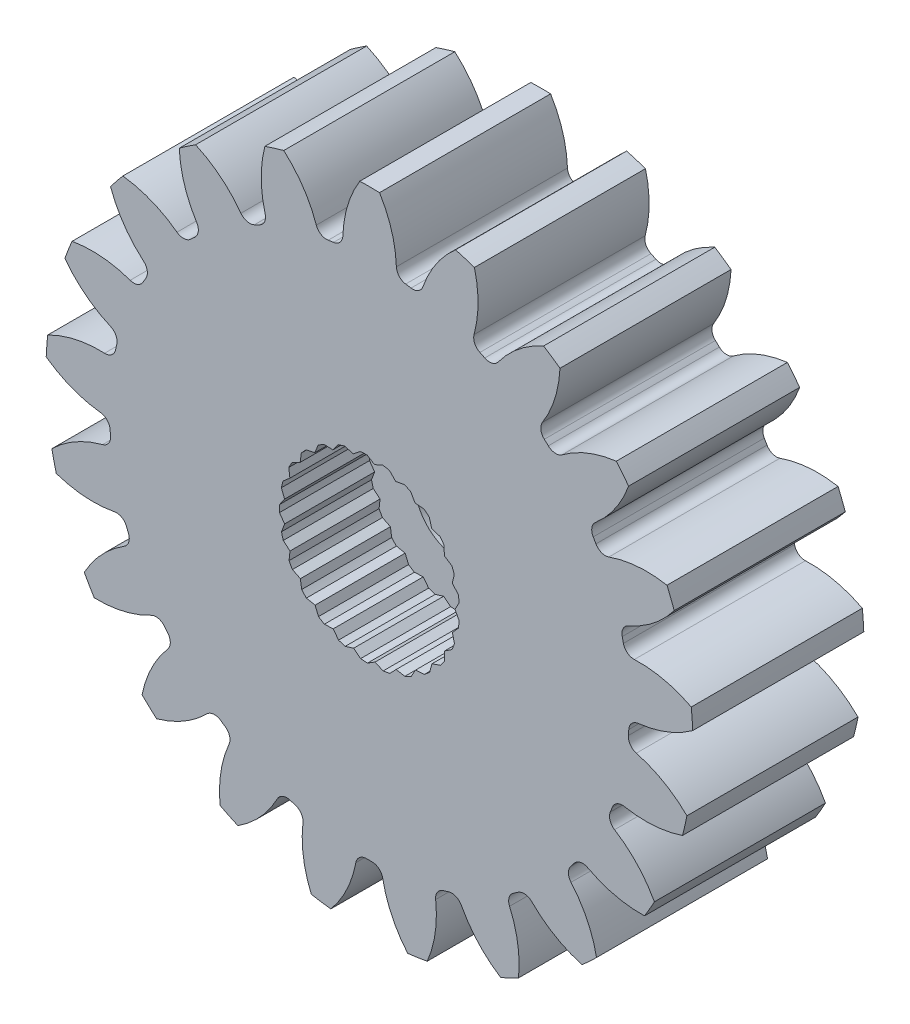
SolidWorks part; units mm, degrees
ref_plane "Front" through (0, 0, 0) normal (0, 0, 1) x (1, 0, 0)
ref_plane "Top" through (0, 0, 0) normal (0, 1, 0) x (1, 0, 0)
ref_plane "Right" through (0, 0, 0) normal (1, 0, 0) x (0, 0, -1)
sketch "Sketch3" plane through (0, 0, 0) normal (0, 0, 1) x (1, 0, 0)
  circle A0 centre (0, 0) radius 9.1281
  dimension "od" = 18.2562
extrude "gearBody" add sketch "Sketch3" along normal blind 4.826
sketch "Sketch2" plane through (0, 0, 0) normal (0, 0, 1) x (1, 0, 0)
  line L0 (0, 0) -> (7.2356, 2.9971) construction
  line L1 (9.5965, -2.6604) -> (0, 0) construction
  line L2 (0, 0) -> (36.3143, 0) construction
  line L3 (8.3344, -0.0188) -> (8.2426, -1.2336) construction
  line L5 (8.2885, -0.6262) -> (0, 0) construction
  line L7 (0, 0) -> (7.8318, 0) construction
  arc A0 (7.8302, -0.1572) -> (7.7649, -1.021) centre (0, 0) ccw construction
  arc A1 (9.1194, 0.3982) -> (8.9561, -1.7638) centre (0, 0) ccw construction
  arc A2 (8.3344, -0.0188) -> (8.2426, -1.2336) centre (0, 0) ccw construction
  arc A3 (7.3041, -0.6287) -> (7.3156, -0.4758) centre (0, 0) ccw
  arc A4 (9.5965, -2.6604) -> (7.5285, -0.9483) centre (6.7032, -4.0501) ccw
  arc A5 (9.5965, -2.6604) -> (9.8873, 1.1884) centre (0, 0) ccw
  arc A6 (9.8873, 1.1884) -> (7.5856, -0.1936) centre (7.2356, 2.9971) cw
  arc A7 (7.3156, -0.4758) -> (7.5856, -0.1936) centre (7.6187, -0.4955) cw
  arc A8 (7.5285, -0.9483) -> (7.3041, -0.6287) centre (7.6066, -0.6548) cw
  point P6 (9.8873, 1.1884)
  point P22 (9.5965, -2.6604)
  dimension "baseDia" = 15.6635
  dimension "od" = 18.2562
  dimension "pd" = 16.6687
  dimension "rd" = 14.6622
  dimension "rFillet" = 0.3037
  dimension "pointX" = 9.8873
  dimension "pointY" = 1.1884
  dimension "CTT" = 1.2148
  dimension "flankCenterAngle" = 22.5
extrude "toothCut" cut sketch "Sketch2" along normal through all
pattern_circular "CirPattern1" count 21 over 360 about axis through (0, 0, 0) along (0, 0, 1) of "toothCut"
sketch "hub1Dia" plane through (0, 0, 0) normal (0, 0, -1) x (-1, 0, 0)
  circle A0 centre (0, 0) radius 12.7
  dimension "hub1Dia" = 25.4
sketch "hub2Dia" plane through (0, 0, 4.826) normal (0, 0, 1) x (1, 0, 0)
  circle A0 centre (0, 0) radius 12.7
  dimension "hub2dia" = 25.4
sketch "boreDia" plane through (0, 0, 0) normal (0, 0, 1) x (1, 0, 0)
  circle A0 centre (0, 0) radius 3.175
  dimension "boreDia" = 6.35
extrude "bore" cut sketch "boreDia" against normal mid plane 25400
sketch "Sketch5" plane through (0, 0, 0) normal (0, 0, -1) x (-1, 0, 0)
  circle A0 centre (0, 0) radius 1.27
  circle A1 centre (0, 0) radius 3.175
  dimension "D1" = 2.54
extrude "Boss-Extrude2" add sketch "Sketch5" against normal up to surface (4.826 mm away) up to face at (3.175, 0, 4.826)
sketch "Sketch4" plane through (0, 0, 4.826) normal (0, 0, 1) x (1, 0, 0)
  line L100 (-2.484, 0.5306) -> (-2.3947, 0.2965)
  line L101 (-2.2457, 0.8827) -> (-2.4359, 0.7196)
  line L102 (-2.274, 1.1317) -> (-2.2457, 0.8827)
  line L103 (-1.9557, 1.4135) -> (-2.1804, 1.3028)
  line L104 (-1.9211, 1.6616) -> (-1.9557, 1.4135)
  line L105 (-1.5427, 1.8554) -> (-1.788, 1.8041)
  line L106 (-1.4475, 2.0872) -> (-1.5427, 1.8554)
  line L107 (-1.0328, 2.1808) -> (-1.2831, 2.1921)
  line L108 (-0.883, 2.3816) -> (-1.0328, 2.1808)
  line L109 (-0.458, 2.3691) -> (-0.6977, 2.4423)
  line L110 (-0.263, 2.5264) -> (-0.458, 2.3691)
  line L111 (0.1455, 2.4086) -> (-0.0684, 2.5391)
  line L112 (0.3736, 2.5124) -> (0.1455, 2.4086)
  line L113 (0.74, 2.2967) -> (0.5652, 2.4763)
  line L114 (0.9866, 2.3405) -> (0.74, 2.2967)
  line L115 (1.2879, 2.0406) -> (1.1633, 2.2579)
  line L116 (1.5377, 2.0216) -> (1.2879, 2.0406)
  line L117 (1.7549, 1.6562) -> (1.6883, 1.8977)
  line L118 (1.9922, 1.5757) -> (1.7549, 1.6562)
  line L119 (2.1116, 1.1677) -> (2.1072, 1.4182)
  line L120 (2.3214, 1.0308) -> (2.1116, 1.1677)
  line L121 (2.3357, 0.6059) -> (2.3937, 0.8496)
  line L122 (2.5049, 0.4211) -> (2.3357, 0.6059)
  line L123 (2.413, 0.006) -> (2.5298, 0.2277)
  line L124 (2.5309, -0.2151) -> (2.413, 0.006)
  line L125 (2.3387, -0.5943) -> (2.5069, -0.4086)
  line L126 (2.3979, -0.8377) -> (2.3387, -0.5943)
  line L127 (2.1174, -1.1572) -> (2.3265, -1.0192)
  line L128 (2.1142, -1.4077) -> (2.1174, -1.1572)
  line L129 (1.7631, -1.6474) -> (2, -1.5658)
  line L130 (1.6977, -1.8893) -> (1.7631, -1.6474)
  line L131 (1.298, -2.0341) -> (1.5477, -2.014)
  line L132 (1.1745, -2.2521) -> (1.298, -2.0341)
  line L133 (0.7514, -2.293) -> (0.9983, -2.3356)
  line L134 (0.5775, -2.4735) -> (0.7514, -2.293)
  line L135 (0.1575, -2.4079) -> (0.3861, -2.5105)
  line L136 (-0.0558, -2.5394) -> (0.1575, -2.4079)
  line L137 (-0.4463, -2.3714) -> (-0.2504, -2.5276)
  line L138 (-0.6855, -2.4457) -> (-0.4463, -2.3714)
  line L139 (-1.022, -2.1859) -> (-0.8711, -2.3859)
  line L140 (-1.2722, -2.1984) -> (-1.022, -2.1859)
  line L141 (-1.5335, -1.8631) -> (-1.4371, -2.0943)
  line L142 (-1.779, -1.813) -> (-1.5335, -1.8631)
  line L143 (-1.9486, -1.4232) -> (-1.9128, -1.6711)
  line L144 (-2.1739, -1.3136) -> (-1.9486, -1.4232)
  line L145 (-2.2413, -0.8939) -> (-2.2683, -1.1429)
  line L146 (-2.4323, -0.7317) -> (-2.2413, -0.8939)
  line L147 (-2.3932, -0.3084) -> (-2.4813, -0.5429)
  line L148 (-2.5379, -0.1038) -> (-2.3932, -0.3084)
  line L149 (-2.3947, 0.2965) -> (-2.5384, 0.0912)
  arc A50 (-2.4359, 0.7196) -> (-2.484, 0.5306) centre (0, 0) ccw
  arc A51 (-2.1804, 1.3028) -> (-2.274, 1.1317) centre (0, 0) ccw
  arc A52 (-1.788, 1.8041) -> (-1.9211, 1.6616) centre (0, 0) ccw
  arc A53 (-1.2831, 2.1921) -> (-1.4475, 2.0872) centre (0, 0) ccw
  arc A54 (-0.6977, 2.4423) -> (-0.883, 2.3816) centre (0, 0) ccw
  arc A55 (-0.0684, 2.5391) -> (-0.263, 2.5264) centre (0, 0) ccw
  arc A56 (0.5652, 2.4763) -> (0.3736, 2.5124) centre (0, 0) ccw
  arc A57 (1.1633, 2.2579) -> (0.9866, 2.3405) centre (0, 0) ccw
  arc A58 (1.6883, 1.8977) -> (1.5377, 2.0216) centre (0, 0) ccw
  arc A59 (2.1072, 1.4182) -> (1.9922, 1.5757) centre (0, 0) ccw
  arc A60 (2.3937, 0.8496) -> (2.3214, 1.0308) centre (0, 0) ccw
  arc A61 (2.5298, 0.2277) -> (2.5049, 0.4211) centre (0, 0) ccw
  arc A62 (2.5069, -0.4086) -> (2.5309, -0.2151) centre (0, 0) ccw
  arc A63 (2.3265, -1.0192) -> (2.3979, -0.8377) centre (0, 0) ccw
  arc A64 (2, -1.5658) -> (2.1142, -1.4077) centre (0, 0) ccw
  arc A65 (1.5477, -2.014) -> (1.6977, -1.8893) centre (0, 0) ccw
  arc A66 (0.9983, -2.3356) -> (1.1745, -2.2521) centre (0, 0) ccw
  arc A67 (0.3861, -2.5105) -> (0.5775, -2.4735) centre (0, 0) ccw
  arc A68 (-0.2504, -2.5276) -> (-0.0558, -2.5394) centre (0, 0) ccw
  arc A69 (-0.8711, -2.3859) -> (-0.6855, -2.4457) centre (0, 0) ccw
  arc A70 (-1.4371, -2.0943) -> (-1.2722, -2.1984) centre (0, 0) ccw
  arc A71 (-1.9128, -1.6711) -> (-1.779, -1.813) centre (0, 0) ccw
  arc A72 (-2.2683, -1.1429) -> (-2.1739, -1.3136) centre (0, 0) ccw
  arc A73 (-2.4813, -0.5429) -> (-2.4323, -0.7317) centre (0, 0) ccw
  arc A74 (-2.5384, 0.0912) -> (-2.5379, -0.1038) centre (0, 0) ccw
extrude "Cut-Extrude1" cut sketch "Sketch4" against normal blind 2.54
